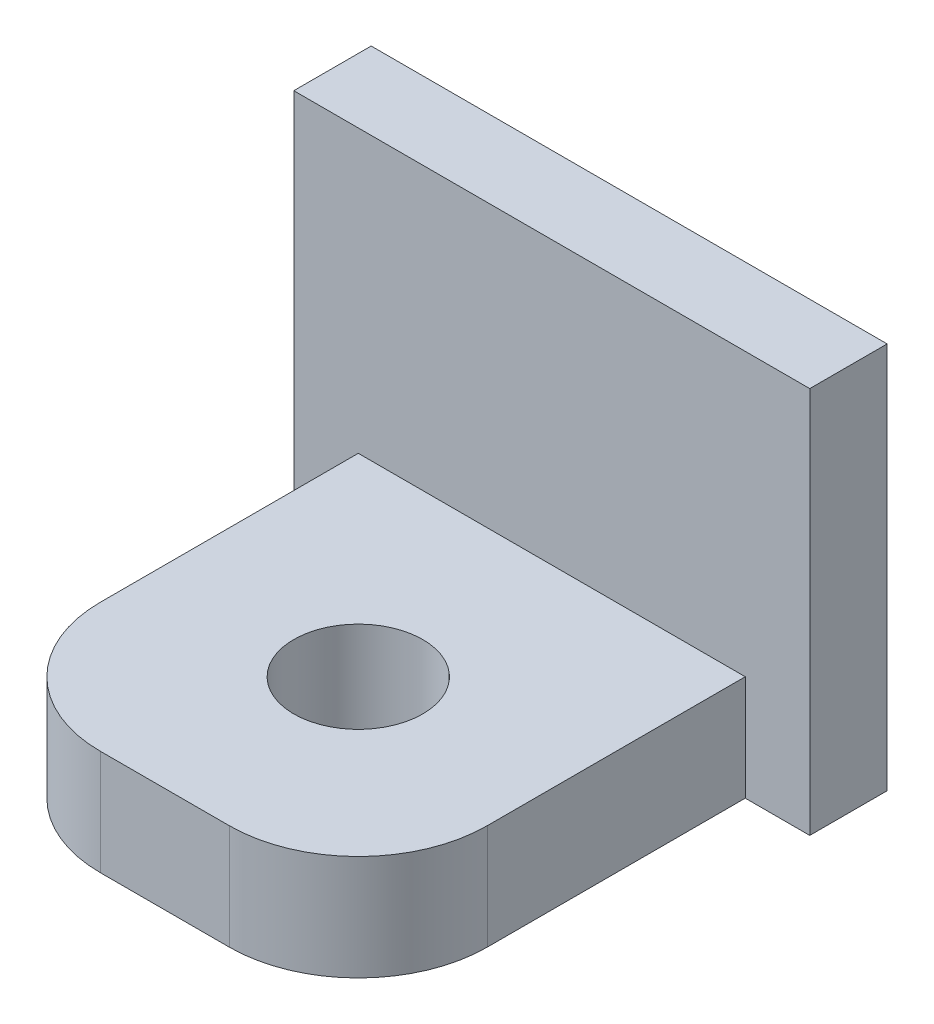
SolidWorks part; units mm, degrees
ref_plane "Спереди" through (0, 0, 0) normal (0, 0, 1) x (1, 0, 0)
ref_plane "Сверху" through (0, 0, 0) normal (0, 1, 0) x (1, 0, 0)
ref_plane "Справа" through (0, 0, 0) normal (1, 0, 0) x (0, 0, -1)
sketch "Эскиз1" plane through (0, 0, 0) normal (0, 0, 1) x (1, 0, 0)
  line L1 (20, 15) -> (-20, 15)
  line L2 (20, 15) -> (20, -15)
  line L3 (20, -15) -> (-20, -15)
  line L4 (-20, 15) -> (-20, -15)
  line L5 (20, 15) -> (-20, -15) construction
  line L6 (20, -15) -> (-20, 15) construction
  point P0 (0, 0)
  dimension "D1" = 30
  dimension "D2" = 40
extrude "Бобышка-Вытянуть2" add sketch "Эскиз1" along normal blind 6 contours L3 L4 L1 L2
sketch "Эскиз2" plane through (0, 0, 6) normal (0, 0, 1) x (1, 0, 0)
  line L0 (20, -15) -> (-20, -15) construction
  line L1 (-15, -15) -> (15, -15)
  line L2 (-15, -15) -> (-15, -6.8452)
  line L3 (-15, -6.8452) -> (15, -6.8452)
  line L4 (15, -15) -> (15, -6.8452)
  line L5 (-20, 15) -> (-20, -15) construction
  line L6 (20, 15) -> (20, -15) construction
  dimension "D1" = 8.1548
  dimension "D2" = 5
  dimension "D3" = 5
extrude "Бобышка-Вытянуть4" add sketch "Эскиз2" along normal blind 30 contours L4 L3 L2 L1
sketch "Эскиз4" plane through (0, -15, 0) normal (0, -1, 0) x (-1, 0, 0)
  line L0 (0, -36) -> (0, 0) construction
  line L1 (15, -36) -> (-15, -36) construction
  line L2 (-20, 0) -> (20, 0) construction
  line L3 (15, -6) -> (-15, -6) construction
  circle A0 centre (0, -21) radius 5
  dimension "D1" = 15
extrude "Вырез-Вытянуть1" cut sketch "Эскиз4" against normal through all
fillet "Скругление1" radius 10 1 edges at (-15, -10.9226, 36)
fillet "Скругление2" radius 10 1 edges at (15, -10.9226, 36)
equation "\"l1\"=40"
equation "\"D2@Эскиз1\"=\"l1\""
equation "\"s\"=30"
equation "\"D1@Эскиз1\"=\"s\""
equation "\"z\"=6"
equation "\"D1@Бобышка-Вытянуть2\"=\"z\""
equation "\"e\"=8.15479"
equation "\"D1@Эскиз2\"=\"e\""
equation "\"q1\"=30"
equation "\"D1@Бобышка-Вытянуть4\"=\"q1\""
